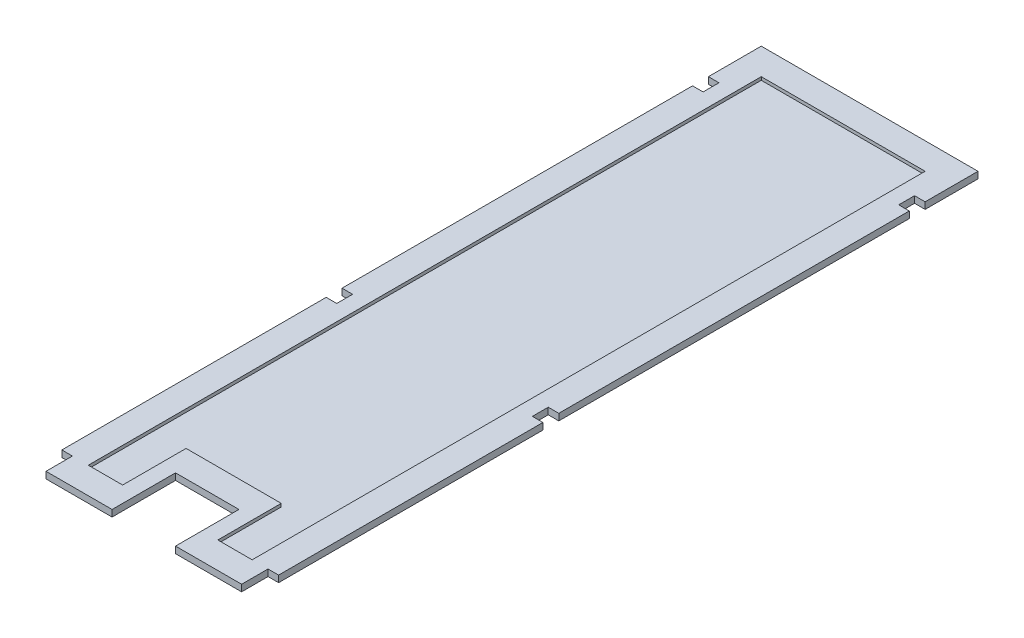
SolidWorks part; units mm, degrees
ref_plane "Front Plane" through (0, 0, 0) normal (0, 0, 1) x (1, 0, 0)
ref_plane "Top Plane" through (0, 0, 0) normal (0, 1, 0) x (1, 0, 0)
ref_plane "Right Plane" through (0, 0, 0) normal (1, 0, 0) x (0, 0, -1)
sketch "Sketch1" plane through (0, 0, 0) normal (0, 1, 0) x (1, 0, 0)
  line L0 (0, 58) -> (0, 124.3)
  line L1 (2, 0) -> (14.5, 0)
  line L2 (0, 5) -> (0, 55)
  line L3 (0, 137.3) -> (41, 137.3)
  line L4 (41, 5) -> (41, 55)
  line L7 (0, 5) -> (2, 5)
  line L8 (2, 0) -> (2, 5)
  line L11 (41, 5) -> (39, 5)
  line L12 (39, 0) -> (39, 5)
  line L13 (0, 55) -> (2, 55)
  line L15 (0, 58) -> (2, 58)
  line L16 (2, 55) -> (2, 58)
  line L17 (41, 55) -> (39, 55)
  line L19 (41, 58) -> (39, 58)
  line L20 (39, 55) -> (39, 58)
  line L21 (41, 58) -> (41, 124.3)
  line L22 (0, 127.3) -> (0, 137.3)
  line L23 (0, 127.3) -> (2, 127.3)
  line L25 (0, 124.3) -> (2, 124.3)
  line L26 (2, 127.3) -> (2, 124.3)
  line L27 (41, 124.3) -> (39, 124.3)
  line L29 (41, 127.3) -> (39, 127.3)
  line L30 (39, 124.3) -> (39, 127.3)
  line L31 (41, 127.3) -> (41, 137.3)
  line L32 (26.5, 0) -> (39, 0)
  line L34 (14.5, 0) -> (14.5, 12)
  line L35 (14.5, 12) -> (26.5, 12)
  line L36 (26.5, 0) -> (26.5, 12)
  dimension "D1" = 137.3
  dimension "D2" = 41
  dimension "D3" = 2
  dimension "D4" = 5
  dimension "D5" = 2
  dimension "D6" = 5
  dimension "D7" = 3
  dimension "D8" = 2
  dimension "D9" = 50
  dimension "D10" = 3
  dimension "D11" = 2
  dimension "D12" = 50
  dimension "D13" = 3
  dimension "D14" = 2
  dimension "D15" = 10
  dimension "D16" = 3
  dimension "D17" = 2
  dimension "D18" = 10
  dimension "D19" = 12
  dimension "D20" = 12
  dimension "D21" = 14.5
extrude "Boss-Extrude1" add sketch "Sketch1" along normal blind 1.25
sketch "Sketch2" plane through (0, 1.25, 0) normal (0, 1, 0) x (1, 0, 0)
  line L0 (0, 124.3) -> (0, 58) construction
  line L1 (5, 132.3) -> (36, 132.3)
  line L2 (5, 132.3) -> (5, 17)
  line L3 (11.5, 17) -> (29.5, 17)
  line L4 (36, 132.3) -> (36, 17)
  line L5 (41, 58) -> (41, 124.3) construction
  line L6 (41, 137.3) -> (0, 137.3) construction
  line L7 (14.5, 12) -> (26.5, 12) construction
  line L10 (5, 17) -> (5, 5)
  line L11 (5, 5) -> (11.5, 5)
  line L12 (11.5, 17) -> (11.5, 5)
  line L14 (36, 17) -> (36, 5)
  line L15 (36, 5) -> (29.5, 5)
  line L16 (29.5, 17) -> (29.5, 5)
  line L17 (26.5, 12) -> (26.5, 0) construction
  line L18 (14.5, 0) -> (14.5, 12) construction
  line L19 (2, 0) -> (14.5, 0) construction
  line L20 (26.5, 0) -> (39, 0) construction
  point P12 (20.5, 12)
  dimension "D1" = 5
  dimension "D2" = 5
  dimension "D3" = 5
  dimension "D4" = 5
  dimension "D5" = 3
  dimension "D6" = 3
  dimension "D7" = 5
  dimension "D8" = 5
extrude "Cut-Extrude1" cut sketch "Sketch2" against normal blind 0.6
